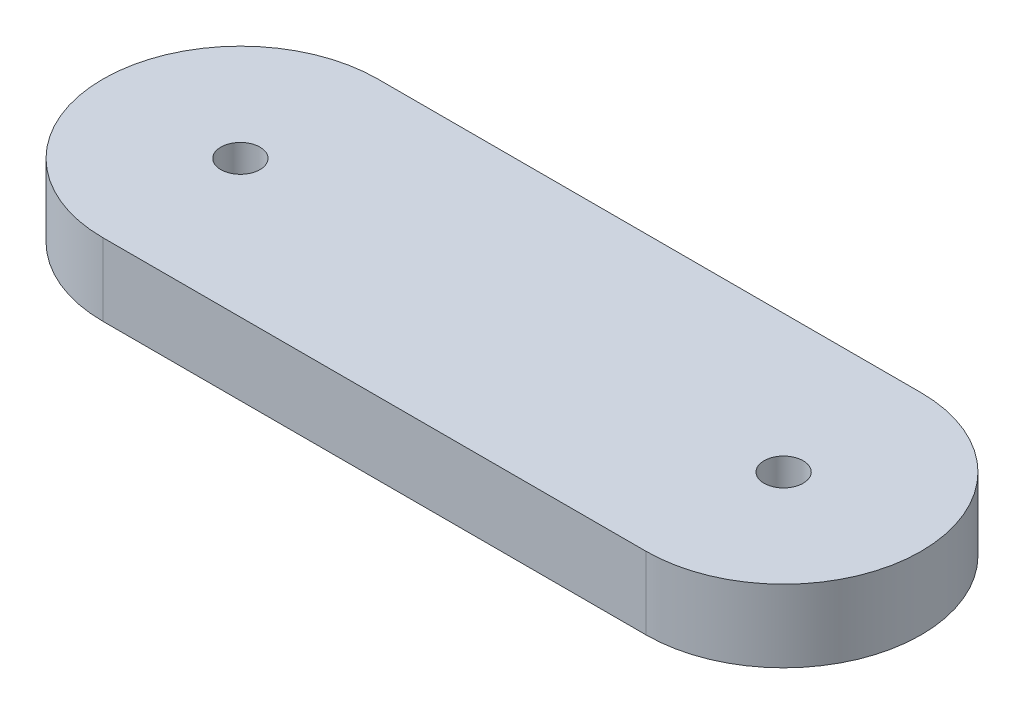
SolidWorks part; units mm, degrees
ref_plane "Front Plane" through (0, 0, 0) normal (0, 0, 1) x (1, 0, 0)
ref_plane "Top Plane" through (0, 0, 0) normal (0, 1, 0) x (1, 0, 0)
ref_plane "Right Plane" through (0, 0, 0) normal (1, 0, 0) x (0, 0, -1)
sketch "Sketch1" plane through (0, 0, 0) normal (0, 1, 0) x (1, 0, 0)
  line L0 (0, 0) -> (75, 0) construction
  line L1 (0, 0) -> (75, 0) construction
  line L2 (0, 18.9772) -> (75, 18.9772)
  line L3 (0, -18.9772) -> (75, -18.9772)
  circle A0 centre (0, 0) radius 60 construction
  circle A1 centre (75, 0) radius 15 construction
  arc A2 (0, 18.9772) -> (0, -18.9772) centre (0, 0) ccw
  arc A3 (75, -18.9772) -> (75, 18.9772) centre (75, 0) ccw
  circle A4 centre (0, 0) radius 2.7
  circle A5 centre (75, 0) radius 2.7
  point P5 (37.5, 0)
  dimension "D1" = 120
  dimension "D2" = 30
  dimension "D3" = 5.4
  dimension "D4" = 5.4
extrude "Boss-Extrude1" add sketch "Sketch1" along normal blind 10 contours L3 A3 L2 A2 A5 A4
equation "\"12c\"=98.9046"
